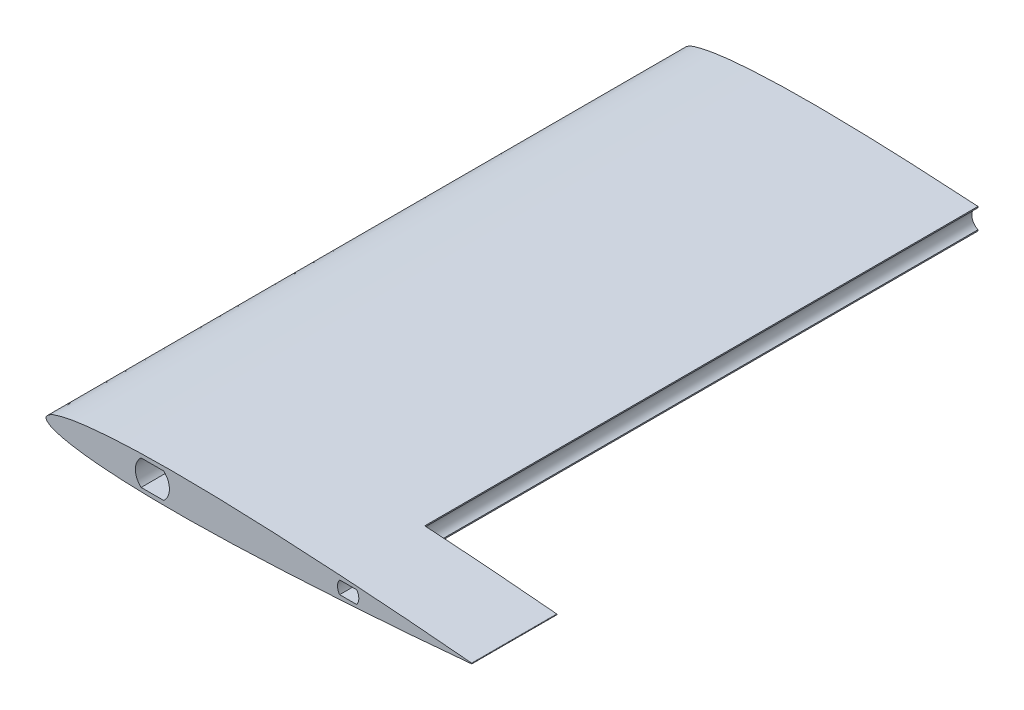
SolidWorks part; units mm, degrees
material "Foam"
ref_plane "Piano frontale" through (0, 0, 0) normal (0, 0, 1) x (1, 0, 0)
ref_plane "Piano superiore" through (0, 0, 0) normal (0, 1, 0) x (1, 0, 0)
ref_plane "Piano destro" through (0, 0, 0) normal (1, 0, 0) x (0, 0, -1)
curve "Curva1"
  spline degree 3 poles (100, 0.084, 0) (98.3335, 0.2367, 0) (95.0012, 0.5422, 0) (88.3356, 1.1109, 0) (80.0033, 1.7636, 0) (70.003, 2.4579, 0) (60.0031, 3.0617, 0) (50.003, 3.5521, 0) (40.0026, 3.9029, 0) (31.667, 4.0253, 0) (24.9992, 3.9769, 0) (19.9978, 3.845, 0) (14.9934, 3.5925, 0) (10.8272, 3.2377, 0) (7.4891, 2.814, 0) (4.9936, 2.4037, 0) (2.8496, 1.8679, 0) (1.1654, 1.321, 0) (-0.6646, 0, 0) (1.1654, -1.321, 0) (2.8496, -1.8679, 0) (4.9936, -2.4037, 0) (7.4891, -2.814, 0) (10.8272, -3.2377, 0) (14.9934, -3.5925, 0) (19.9978, -3.845, 0) (24.9992, -3.9769, 0) (31.667, -4.0253, 0) (40.0026, -3.9029, 0) (50.003, -3.5521, 0) (60.0031, -3.0617, 0) (70.003, -2.4579, 0) (80.0033, -1.7636, 0) (88.3356, -1.1109, 0) (95.0012, -0.5422, 0) (98.3335, -0.2367, 0) (100, -0.084, 0) knots 0 0 0 0 0.024876 0.049742 0.099443 0.149112 0.198751 0.248359 0.297937 0.347491 0.372267 0.397051 0.421859 0.446731 0.45922 0.471791 0.48456 0.491195 0.5 0.508805 0.51544 0.528209 0.54078 0.553269 0.578141 0.602949 0.627733 0.652509 0.702063 0.751641 0.801249 0.850888 0.900557 0.950258 0.975124 1 1 1 1
sketch "Schizzo1" plane through (0, 0, 0) normal (0, 0, 1) x (1, 0, 0)
  line L0 (70, 2.443) -> (70, -2.443) construction
  arc A1 (70, -2.443) -> (70, 2.443) centre (70, 0) cw
  spline S0 degree 3 poles (774.5938, 2905.893) (370.1816, -60.6448) (232.5901, -11.1972) (88.3356, 1.1109) (80.0033, 1.7636) (70.003, 2.4579) (60.0031, 3.0617) (50.003, 3.5521) (40.0026, 3.9029) (31.667, 4.0253) (24.9992, 3.9769) (19.9978, 3.845) (14.9934, 3.5925) (10.8272, 3.2377) (7.4891, 2.814) (4.9936, 2.4037) (2.8496, 1.8679) (1.1654, 1.321) (-0.6646, 0) (1.1654, -1.321) (2.8496, -1.8679) (4.9936, -2.4037) (7.4891, -2.814) (10.8272, -3.2377) (14.9934, -3.5925) (19.9978, -3.845) (24.9992, -3.9769) (31.667, -4.0253) (40.0026, -3.9029) (50.003, -3.5521) (60.0031, -3.0617) (70.003, -2.4579) (80.0033, -1.7636) (88.3356, -1.1109) (232.5893, 11.1971) (370.1799, 60.6442) (774.5865, -2905.8392) knots -2.052665 -2.052665 -2.052665 -2.052665 0.024876 0.049742 0.099443 0.149112 0.198751 0.248359 0.297937 0.347491 0.372267 0.397051 0.421859 0.446731 0.45922 0.471791 0.48456 0.491195 0.5 0.508805 0.51544 0.528209 0.54078 0.553269 0.578141 0.602949 0.627733 0.652509 0.702063 0.751641 0.801249 0.850888 0.900557 0.950258 0.975124 3.052652 3.052652 3.052652 3.052652 only from (100, 0.084) to (100, -0.084) construction
  spline S1 degree 3 poles (70, 2.443) (66.6677, 2.6593) (60.0031, 3.0617) (50.003, 3.5521) (40.0026, 3.9029) (31.667, 4.0253) (24.9992, 3.9769) (19.9978, 3.845) (14.9934, 3.5925) (10.8272, 3.2377) (7.4891, 2.814) (4.9936, 2.4037) (2.8496, 1.8679) (1.1654, 1.321) (-0.6646, 0) (1.1654, -1.321) (2.8496, -1.8679) (4.9936, -2.4037) (7.4891, -2.814) (10.8272, -3.2377) (14.9934, -3.5925) (19.9978, -3.845) (24.9992, -3.9769) (31.667, -4.0253) (40.0026, -3.9029) (50.003, -3.5521) (60.0031, -3.0617) (66.6677, -2.6593) (70, -2.443) knots 0.149112 0.149112 0.149112 0.149112 0.198751 0.248359 0.297937 0.347491 0.372267 0.397051 0.421859 0.446731 0.45922 0.471791 0.48456 0.491195 0.5 0.508805 0.51544 0.528209 0.54078 0.553269 0.578141 0.602949 0.627733 0.652509 0.702063 0.751641 0.801249 0.850888 0.850888 0.850888 0.850888
  dimension "D1" = 4.886
extrude "CorpoFoam" add sketch "Schizzo1" along normal blind 130
sketch "Schizzo7" plane through (0, 0, 130) normal (0, 0, 1) x (1, 0, 0)
  arc A0 (100, 0.084) -> (100, -0.084) centre (100, 0) cw
  spline S0 degree 3 poles (633.0503, 1915.9881) (335.6221, -48.8321) (214.9188, -9.6895) (88.3356, 1.1109) (80.0033, 1.7636) (70.003, 2.4579) (60.0031, 3.0617) (50.003, 3.5521) (40.0026, 3.9029) (31.667, 4.0253) (24.9992, 3.9769) (19.9978, 3.845) (14.9934, 3.5925) (10.8272, 3.2377) (7.4891, 2.814) (4.9936, 2.4037) (2.8496, 1.8679) (1.1654, 1.321) (-0.6646, 0) (1.1654, -1.321) (2.8496, -1.8679) (4.9936, -2.4037) (7.4891, -2.814) (10.8272, -3.2377) (14.9934, -3.5925) (19.9978, -3.845) (24.9992, -3.9769) (31.667, -4.0253) (40.0026, -3.9029) (50.003, -3.5521) (60.0031, -3.0617) (70.003, -2.4579) (80.0033, -1.7636) (88.3356, -1.1109) (214.9185, 9.6894) (335.6215, 48.8319) (633.0478, -1915.9718) knots -1.78903 -1.78903 -1.78903 -1.78903 0.024876 0.049742 0.099443 0.149112 0.198751 0.248359 0.297937 0.347491 0.372267 0.397051 0.421859 0.446731 0.45922 0.471791 0.48456 0.491195 0.5 0.508805 0.51544 0.528209 0.54078 0.553269 0.578141 0.602949 0.627733 0.652509 0.702063 0.751641 0.801249 0.850888 0.900557 0.950258 0.975124 2.789025 2.789025 2.789025 2.789025 only from (100, 0.084) to (100, -0.084) construction
  spline S1 degree 3 poles (100, 0.084) (98.3335, 0.2367) (95.0012, 0.5422) (88.3356, 1.1109) (80.0033, 1.7636) (70.003, 2.4579) (60.0031, 3.0617) (50.003, 3.5521) (40.0026, 3.9029) (31.667, 4.0253) (24.9992, 3.9769) (19.9978, 3.845) (14.9934, 3.5925) (10.8272, 3.2377) (7.4891, 2.814) (4.9936, 2.4037) (2.8496, 1.8679) (1.1654, 1.321) (-0.6646, 0) (1.1654, -1.321) (2.8496, -1.8679) (4.9936, -2.4037) (7.4891, -2.814) (10.8272, -3.2377) (14.9934, -3.5925) (19.9978, -3.845) (24.9992, -3.9769) (31.667, -4.0253) (40.0026, -3.9029) (50.003, -3.5521) (60.0031, -3.0617) (70.003, -2.4579) (80.0033, -1.7636) (88.3356, -1.1109) (95.0012, -0.5422) (98.3335, -0.2367) (100, -0.084) knots 0 0 0 0 0.024876 0.049742 0.099443 0.149112 0.198751 0.248359 0.297937 0.347491 0.372267 0.397051 0.421859 0.446731 0.45922 0.471791 0.48456 0.491195 0.5 0.508805 0.51544 0.528209 0.54078 0.553269 0.578141 0.602949 0.627733 0.652509 0.702063 0.751641 0.801249 0.850888 0.900557 0.950258 0.975124 1 1 1 1
extrude "FoamLaterale" add sketch "Schizzo7" along normal blind 20
sketch "Schizzo2" plane through (0, 0, 150) normal (0, 0, 1) x (1, 0, 0)
  line L0 (25, 0) -> (0, 0) construction
  circle A0 centre (25, 0) radius 3
  dimension "D1" = 6
  dimension "D2" = 25
extrude "ForoLongherone" cut sketch "Schizzo2" against normal through all
sketch "Schizzo5" plane through (0, 0, 150) normal (0, 0, -1) x (-1, 0, 0)
  line L1 (-27.6458, 3) -> (-22.3542, 3)
  line L3 (-27.6458, -3) -> (-22.3542, -3)
  arc A0 (-27.6458, 3) -> (-27.6458, -3) centre (-25, 0) ccw
  circle A1 centre (-25, 0) radius 3 construction
  arc A2 (-22.3542, -3) -> (-22.3542, 3) centre (-25, 0) ccw
  dimension "D1" = 8
sketch "Schizzo6" plane through (0, 0, 0) normal (0, 0, -1) x (-1, 0, 0)
  line L0 (-72, 0) -> (-70, 0) construction
  line L1 (-72, 2.5074) -> (-69, 2.5074)
  line L2 (-72, 2.5074) -> (-72, -2.5074)
  line L3 (-72, -2.5074) -> (-69, -2.5074)
  line L4 (-69, 2.5074) -> (-69, -2.5074)
  spline S0 degree 3 poles (-70, 2.443) (-66.6677, 2.6593) (-60.0031, 3.0617) (-50.003, 3.5521) (-40.0026, 3.9029) (-31.667, 4.0253) (-24.9992, 3.9769) (-19.9978, 3.845) (-14.9934, 3.5925) (-10.8272, 3.2377) (-7.4891, 2.814) (-4.9936, 2.4037) (-2.8496, 1.8679) (-1.1654, 1.321) (0.6646, 0) (-1.1654, -1.321) (-2.8496, -1.8679) (-4.9936, -2.4037) (-7.4891, -2.814) (-10.8272, -3.2377) (-14.9934, -3.5925) (-19.9978, -3.845) (-24.9992, -3.9769) (-31.667, -4.0253) (-40.0026, -3.9029) (-50.003, -3.5521) (-60.0031, -3.0617) (-66.6677, -2.6593) (-70, -2.443) knots 0.149112 0.149112 0.149112 0.149112 0.198751 0.248359 0.297937 0.347491 0.372267 0.397051 0.421859 0.446731 0.45922 0.471791 0.48456 0.491195 0.5 0.508805 0.51544 0.528209 0.54078 0.553269 0.578141 0.602949 0.627733 0.652509 0.702063 0.751641 0.801249 0.850888 0.850888 0.850888 0.850888 construction
  dimension "D1" = 3
  dimension "D2" = 1
extrude "Taglio-Estrusione1" cut sketch "Schizzo5" along normal blind 15
extrude "SmussoPosteriore" cut sketch "Schizzo6" against normal up to surface (130 mm away) up to face at (84.4102, -0.5898, 130)
sketch "Schizzo8" plane through (0, 0, 150) normal (0, 0, 1) x (1, 0, 0)
  line L0 (69, 1.5) -> (73, 1.5)
  line L9 (73, -1.5) -> (69, -1.5)
  arc A1 (100, -0.084) -> (100, 0.084) centre (100, 0) ccw construction
  arc A2 (69, 1.5) -> (69, -1.5) centre (71, 0) ccw
  arc A3 (73, -1.5) -> (73, 1.5) centre (71, 0) ccw
  point P6 (100.084, 0)
  dimension "D1" = 3
  dimension "D3" = 5
  dimension "D2" = 29
  dimension "D4" = 4
extrude "ForoPerno" cut sketch "Schizzo8" against normal through all
